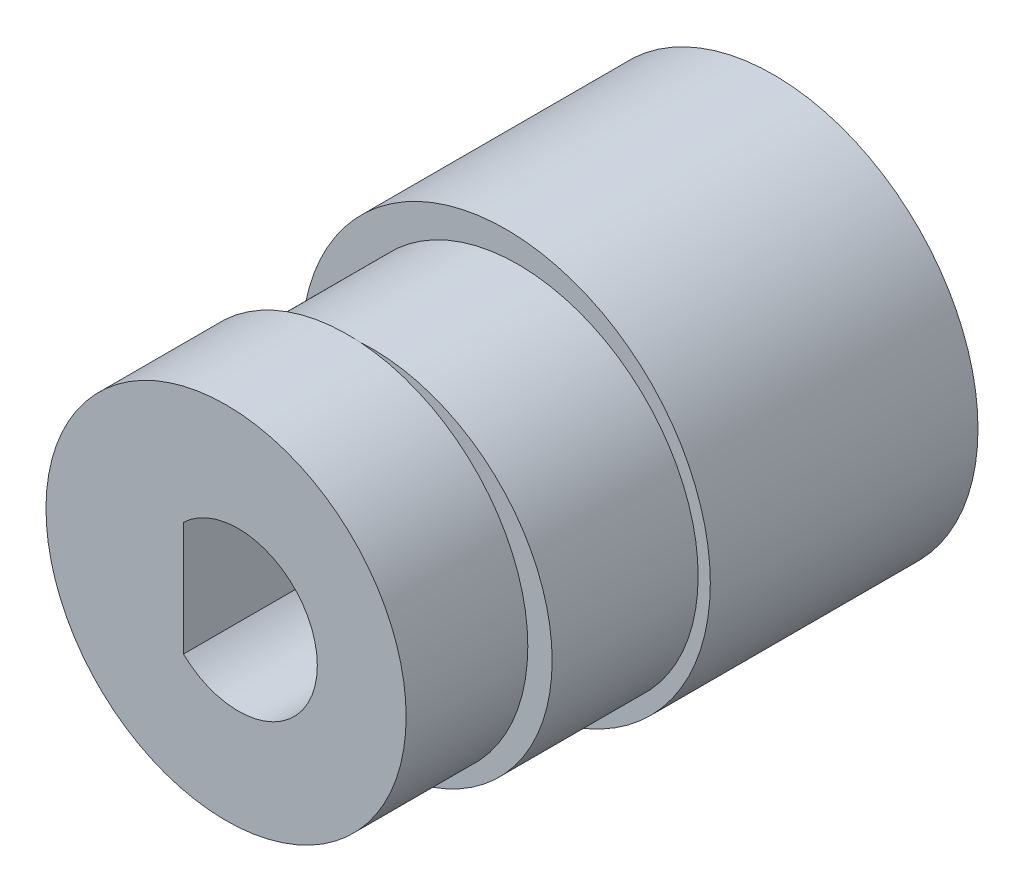
SolidWorks part; units mm, degrees
ref_plane "Plan de face" through (0, 0, 0) normal (0, 0, 1) x (1, 0, 0)
ref_plane "Plan de dessus" through (0, 0, 0) normal (0, 1, 0) x (1, 0, 0)
ref_plane "Plan de droite" through (0, 0, 0) normal (1, 0, 0) x (0, 0, -1)
sketch "Esquisse1" plane through (0, 0, 0) normal (0, 0, 1) x (1, 0, 0)
  circle A0 centre (0, 0) radius 8.4
  dimension "D1" = 16.8
extrude "Boss.-Extru.1" add sketch "Esquisse1" along normal blind 11
sketch "Esquisse3" plane through (0, 0, 11) normal (0, 0, 1) x (1, 0, 0)
  circle A0 centre (0.5, 0) radius 7.4
  dimension "D1" = 14.8
  dimension "D2" = 0.5
extrude "Boss.-Extru.2" add sketch "Esquisse3" along normal blind 6
sketch "Esquisse4" plane through (0, 0, 17) normal (0, 0, 1) x (1, 0, 0)
  circle A0 centre (-0.5, 0) radius 7.4
  dimension "D1" = 14.8
  dimension "D2" = 0.5
extrude "Boss.-Extru.3" add sketch "Esquisse4" along normal blind 5 contours A0
sketch "Esquisse5" plane through (0, 0, 0) normal (0, 0, -1) x (-1, 0, 0)
  line L0 (2.25, 2.3452) -> (2.25, -2.3452)
  arc A1 (2.25, 2.3452) -> (2.25, -2.3452) centre (0, 0) ccw
  dimension "D1" = 3.25
  dimension "D2" = 2.25
extrude "Enlèv. mat.-Extru.1" cut sketch "Esquisse5" against normal through all contours A1 L0
